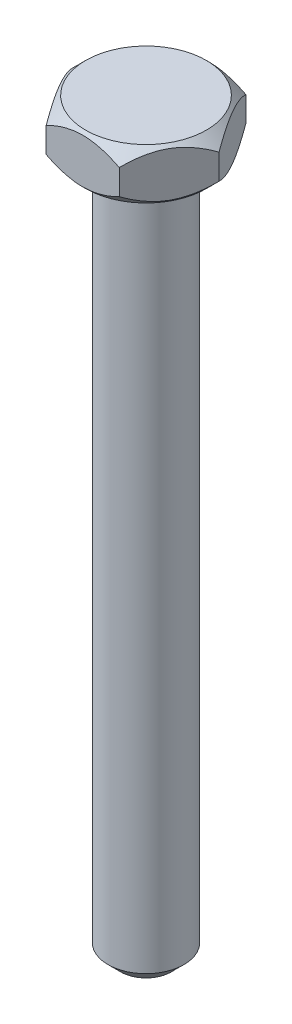
SolidWorks part; units mm, degrees
ref_plane "Спереди" through (0, 0, 0) normal (0, 0, 1) x (1, 0, 0)
ref_plane "Сверху" through (0, 0, 0) normal (0, 1, 0) x (1, 0, 0)
ref_plane "Справа" through (0, 0, 0) normal (1, 0, 0) x (0, 0, -1)
sketch "Эскиз1" plane through (0, 0, 0) normal (0, 1, 0) x (1, 0, 0)
  line L0 (-2.8868, 5) -> (2.8868, 5)
  line L1 (2.8868, 5) -> (5.7735, 0)
  line L2 (5.7735, 0) -> (2.8868, -5)
  line L3 (2.8868, -5) -> (-2.8868, -5)
  line L4 (-2.8868, -5) -> (-5.7735, 0)
  line L5 (-5.7735, 0) -> (-2.8868, 5)
  dimension "D1" = 5
  dimension "D2" = 120
  dimension "D3" = 120
  dimension "D4" = 120
  dimension "D5" = 120
  dimension "D6" = 5
  dimension "D7" = 5
  dimension "D8" = 5
  dimension "D9" = 5
  dimension "D10" = 5
extrude "Вытянуть1" add sketch "Эскиз1" against normal blind 4
sketch "Эскиз2" plane through (0, -4, 0) normal (0, -1, 0) x (1, 0, 0)
  circle A0 centre (0, 0) radius 3
  dimension "D1" = 6
extrude "Вытянуть2" add sketch "Эскиз2" along normal blind 55
chamfer "Фаска2" distance 1 angle 45 1 edges at (0, -59, -3)
ref_axis "Ось1" through (0, -4, 0) along (0, -1, 0)
ref_plane "Плоскость1" through (0, 0, 0) normal (0, 0, 1) x (1, 0, 0)
sketch "Эскиз3" plane through (0, 0, 0) normal (0, 0, 1) x (1, 0, 0)
  line L0 (-5.7735, -1) -> (-4.7735, 0)
  line L1 (-5.7735, -4) -> (-5.7735, 0) construction
  line L2 (-5.7735, 0) -> (-2.8868, 0) construction
  line L3 (-4.7735, 0) -> (-5.7735, 0)
  line L4 (-5.7735, 0) -> (-5.7735, -1)
  line L5 (-5.7735, -3) -> (-4.7735, -4)
  line L6 (-5.7735, -4) -> (-2.8868, -4) construction
  line L7 (-4.7735, -4) -> (-5.7735, -4)
  line L8 (-5.7735, -4) -> (-5.7735, -3)
  dimension "D1" = 1
  dimension "D2" = 1
  dimension "D3" = 1
  dimension "D4" = 1
revolve "Вырез-Повернуть1" cut sketch "Эскиз3" angle 360 about axis through (0, -4, 0) along (0, -1, 0)
